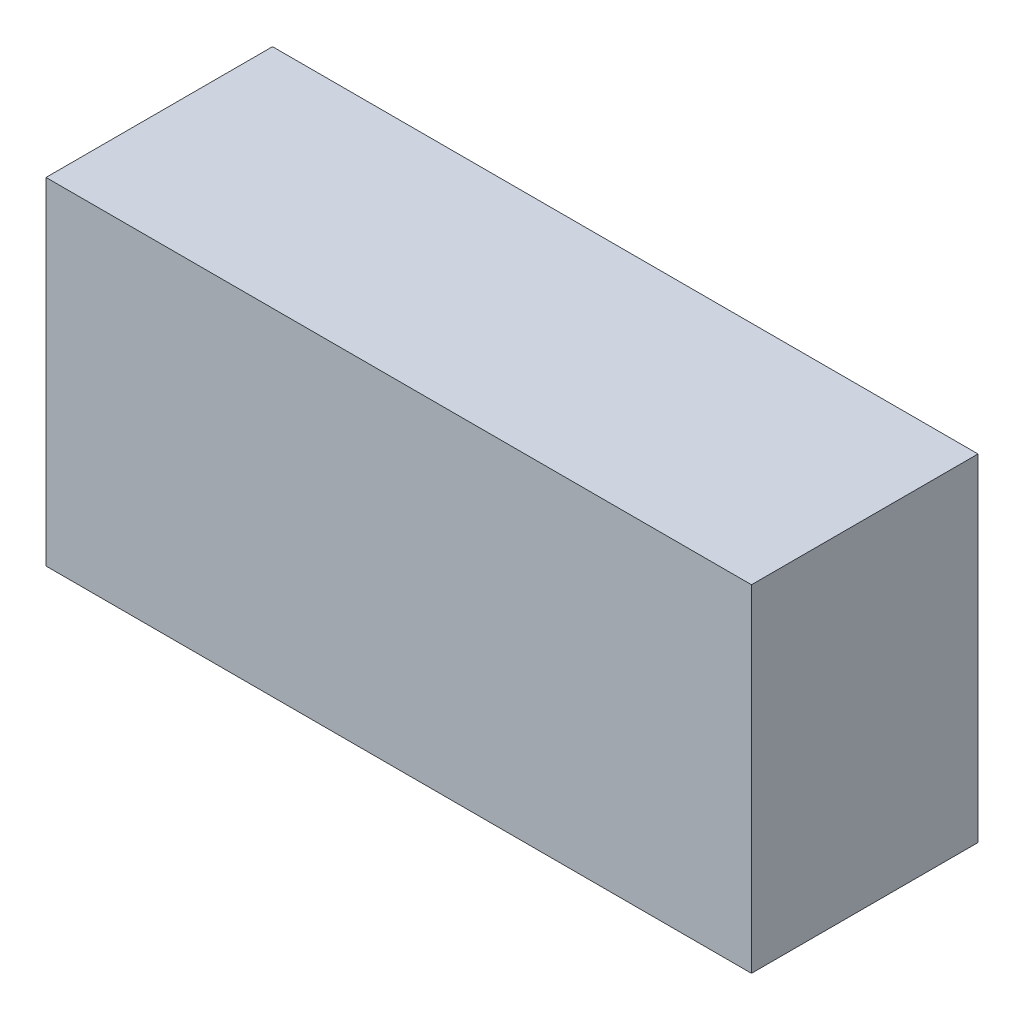
SolidWorks part; units mm, degrees
ref_plane "前视基准面" through (0, 0, 0) normal (0, 0, 1) x (1, 0, 0)
ref_plane "上视基准面" through (0, 0, 0) normal (0, 1, 0) x (1, 0, 0)
ref_plane "右视基准面" through (0, 0, 0) normal (1, 0, 0) x (0, 0, -1)
other "Configuration Table"
sketch "草图1" plane through (0, 0, 0) normal (0, 1, 0) x (1, 0, 0)
  line L0 (0, 0) -> (0, 35)
  line L1 (0, 35) -> (109, 35)
  line L2 (109, 35) -> (109, 0)
  line L3 (109, 0) -> (0, 0)
  dimension "D1" = 109
  dimension "D2" = 35
extrude "凸台-拉伸1" add sketch "草图1" along normal blind 52
